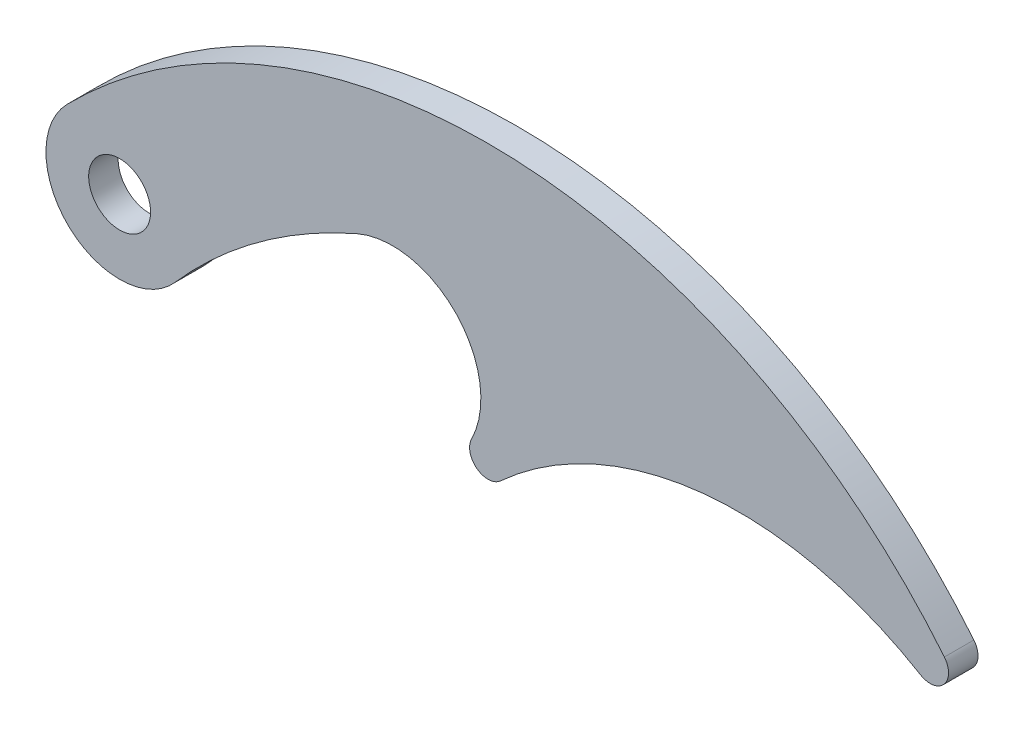
SolidWorks part; units mm, degrees
ref_plane "Front Plane" through (0, 0, 0) normal (0, 0, 1) x (1, 0, 0)
ref_plane "Top Plane" through (0, 0, 0) normal (0, 1, 0) x (1, 0, 0)
ref_plane "Right Plane" through (0, 0, 0) normal (1, 0, 0) x (0, 0, -1)
sketch "Sketch1" plane through (0, 0, 0) normal (0, 0, 1) x (1, 0, 0)
  line L0 (-10.7179, 0) -> (69.4329, 0) construction
  line L1 (55, 9.3211) -> (55, -10.0077) construction
  circle A0 centre (0, 0) radius 2.1
  arc A1 (-3.5694, 3.5013) -> (3.7624, -3.293) centre (0, 0) ccw
  arc A2 (54.3572, -1.0721) -> (55.9682, 0.7906) centre (55, 0) ccw
  arc A3 (-3.5694, 3.5013) -> (55.9682, 0.7906) centre (24.9858, -24.5094) cw
  arc A4 (3.7624, -3.293) -> (16.1181, 5.7418) centre (30.0994, -26.3443) cw
  arc A5 (23.8819, -2.4411) -> (25.8424, -3.9235) centre (25, -3) ccw
  arc A7 (23.8819, -2.4411) -> (16.1181, 5.7418) centre (18.5149, 0.2414) ccw
  arc A8 (3.7624, -3.293) -> (16.1181, 5.7418) centre (30.0994, -26.3443) cw
  arc A9 (25.8424, -3.9235) -> (54.3572, -1.0721) centre (42.0156, -21.6556) cw
  dimension "D1" = 4.2
  dimension "D2" = 10
  dimension "D4" = 2.5
  dimension "D5" = 40
  dimension "D6" = 35
  dimension "D7" = 2.5
  dimension "D10" = 6
  dimension "D11" = 24
  dimension "D3" = 55
  dimension "D8" = 30
  dimension "D9" = 3
extrude "Boss-Extrude1" add sketch "Sketch1" along normal blind 2 contours A5 A9 A2 A3 A1 A4 A7 A0
